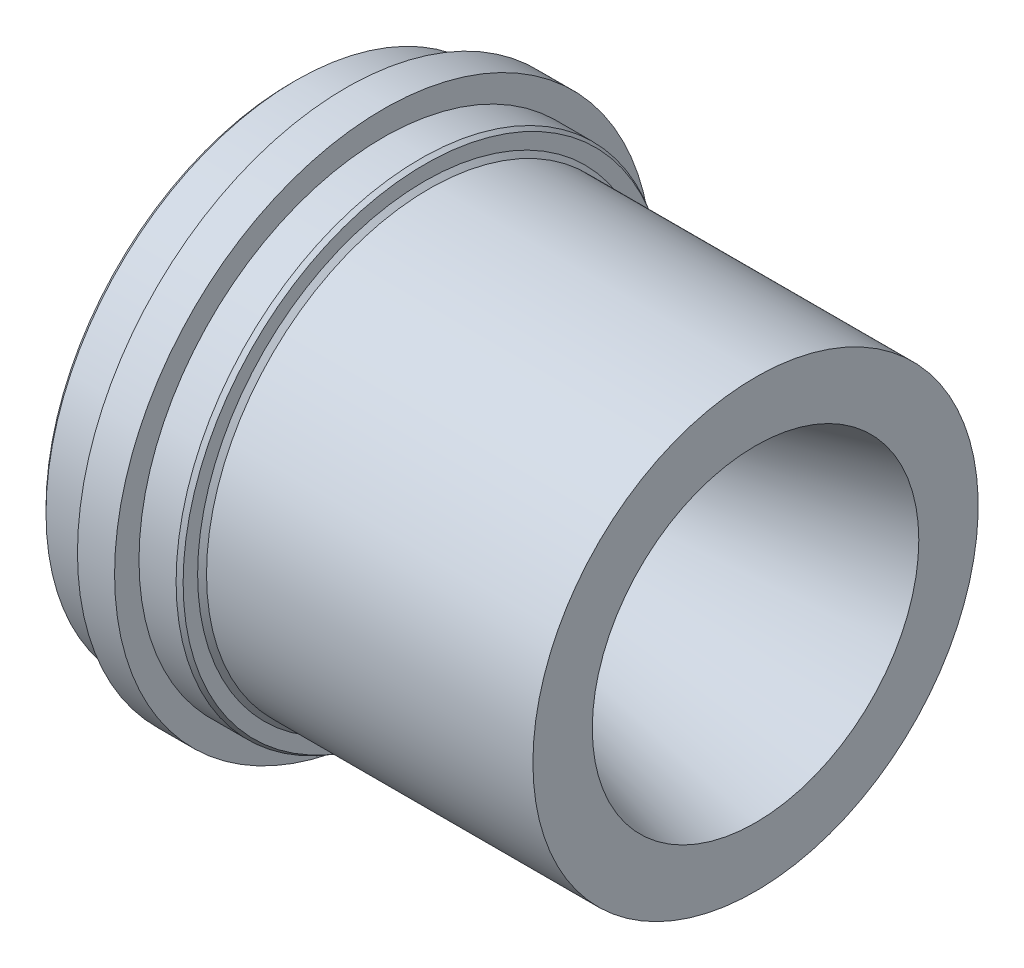
SolidWorks part; units mm, degrees
material "C (Graphite)"
ref_plane "Front Plane" through (0, 0, 0) normal (0, 0, 1) x (1, 0, 0)
ref_plane "Top Plane" through (0, 0, 0) normal (0, 1, 0) x (1, 0, 0)
ref_plane "Right Plane" through (0, 0, 0) normal (1, 0, 0) x (0, 0, -1)
sketch "Sketch1" plane through (0, 0, 0) normal (0, 0, 1) x (1, 0, 0)
  line L0 (0, 36.4109) -> (0, 41.9989)
  line L1 (0.762, 42.7609) -> (9.3472, 42.7609)
  line L2 (9.3472, 42.7609) -> (9.3472, 45.9613)
  line L3 (9.3472, 45.9613) -> (15.6972, 45.9613)
  line L4 (15.6972, 45.9613) -> (15.6972, 41.783)
  line L5 (15.6972, 41.783) -> (22.0472, 41.783)
  line L6 (22.8092, 41.3431) -> (22.8092, 38.862)
  line L7 (23.5712, 38.1) -> (104.1146, 38.1)
  line L8 (104.8766, 37.338) -> (104.8766, 34.7599)
  line L9 (104.8766, 34.7599) -> (22.6314, 12.7224)
  line L11 (10.0664, 18.9754) -> (0, 36.4109)
  line L12 (0, 0) -> (104.8766, 0) construction
  line L13 (0, 41.9989) -> (0.762, 42.7609)
  line L14 (22.8092, 38.862) -> (23.5712, 38.1)
  line L15 (104.1146, 38.1) -> (104.8766, 37.338)
  line L16 (22.0472, 41.783) -> (22.8092, 41.3431)
  line L17 (21.0312, 0) -> (21.0312, 12.6254) construction
  line L18 (22.6314, 0) -> (22.6314, 12.7224) construction
  line L19 (79.4244, 0) -> (79.4244, 27.94) construction
  arc A1 (10.0664, 18.9754) -> (22.6314, 12.7224) centre (21.0649, 25.3254) ccw
  point P1 (0, 42.7609)
  point P7 (22.8092, 41.783)
  point P8 (22.8092, 38.1)
  point P9 (104.8766, 38.1)
  dimension "D21" = 21.0312
  dimension "D24" = 12.7
  dimension "D25" = 27.94
  dimension "D1" = 104.8766
  dimension "D2" = 45.9613
  dimension "D3" = 42.7609
  dimension "D4" = 0.762
  dimension "D5" = 38.1
  dimension "D6" = 34.7599
  dimension "D7" = 60
  dimension "D8" = 15
  dimension "D9" = 36.4109
  dimension "D10" = 82.0674
  dimension "D11" = 89.1794
  dimension "D12" = 95.5294
  dimension "D13" = 0.762
  dimension "D14" = 45
  dimension "D15" = 0.762
  dimension "D16" = 45
  dimension "D17" = 0.762
  dimension "D18" = 45
  dimension "D19" = 30
  dimension "D20" = 41.783
  dimension "D22" = 1.6002
  dimension "D23" = 12.7224
revolve "Revolve1" add sketch "Sketch1" angle 360 about L12
sketch "Sketch2" plane through (0, 0, 0) normal (0, 0, 1) x (1, 0, 0)
  line L0 (79.4244, 38.1) -> (104.8766, 38.1)
  line L1 (104.1146, 38.1) -> (23.5712, 38.1) construction
  line L2 (104.8766, 38.1) -> (104.8766, -38.1)
  line L3 (104.8766, -38.1) -> (79.4244, -38.1)
  line L4 (23.5712, -38.1) -> (104.1146, -38.1) construction
  line L5 (79.4244, -38.1) -> (79.4244, 38.1)
  line L6 (79.4244, 0) -> (79.4244, 27.94) construction
extrude "Cut-Extrude1" cut sketch "Sketch2" against normal through all both and the other way through all
